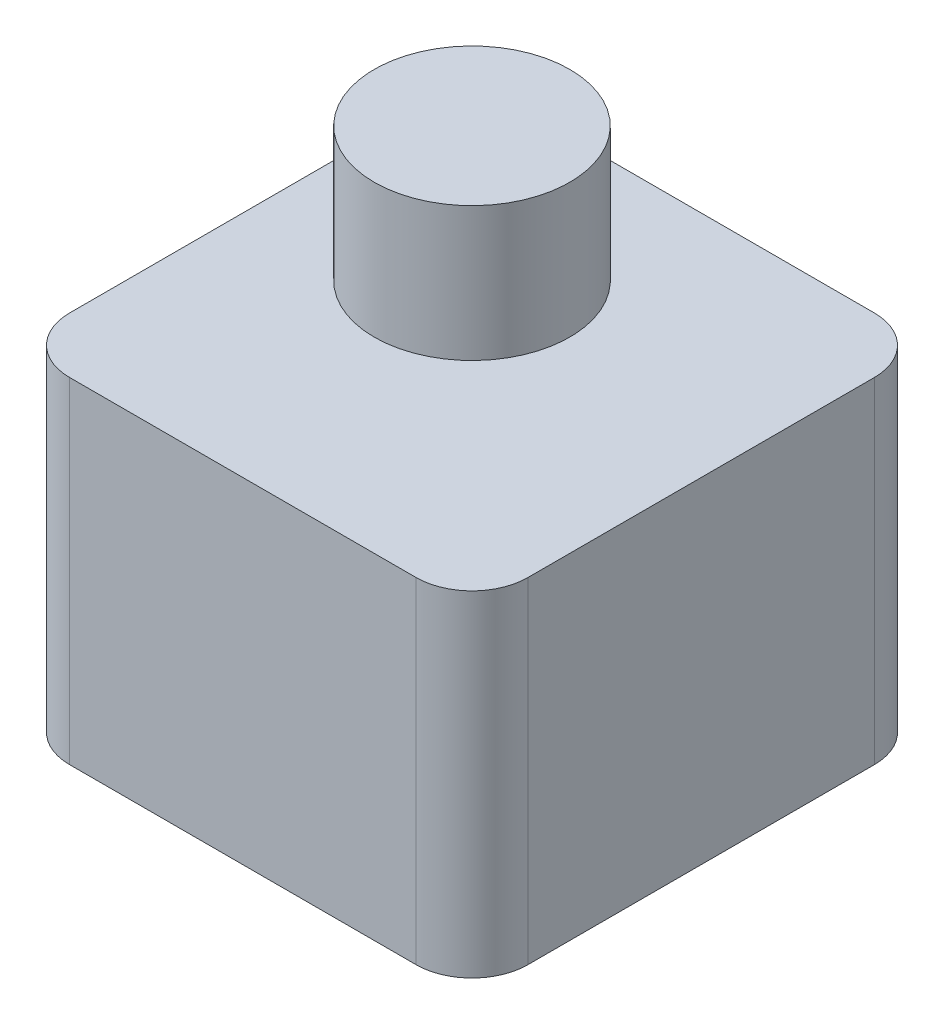
SolidWorks part; units mm, degrees
ref_plane "Alzado" through (0, 0, 0) normal (0, 0, 1) x (1, 0, 0)
ref_plane "Planta" through (0, 0, 0) normal (0, 1, 0) x (1, 0, 0)
ref_plane "Vista lateral" through (0, 0, 0) normal (1, 0, 0) x (0, 0, -1)
sketch "Croquis2" plane through (0, 0, 0) normal (0, 1, 0) x (1, 0, 0)
  line L1 (5, 41) -> (36, 41)
  line L2 (0, 36) -> (0, 5)
  line L3 (5, 0) -> (36, 0)
  line L4 (41, 36) -> (41, 5)
  arc A0 (0, 5) -> (5, 0) centre (5, 5) ccw
  arc A1 (36, 0) -> (41, 5) centre (36, 5) ccw
  arc A2 (36, 41) -> (41, 36) centre (36, 36) cw
  arc A3 (5, 41) -> (0, 36) centre (5, 36) ccw
  dimension "D1" = 5
  dimension "D2" = 41
  dimension "D3" = 41
extrude "Saliente-Extruir2" add sketch "Croquis2" along normal blind 30
sketch "Croquis3" plane through (0, 30, 0) normal (0, 1, 0) x (1, 0, 0)
  circle A3 centre (20.5, 20.5) radius 1.5
extrude "Saliente-Extruir3" add sketch "Croquis3" along normal blind 17 separate body
ref_plane "Plano2" through (0, 35, 0) normal (0, 1, 0) x (1, 0, 0)
sketch "Croquis6" plane through (0, 35, 0) normal (0, 1, 0) x (1, 0, 0)
  circle A0 centre (20.5, 20.5) radius 8.75
extrude "Saliente-Extruir4" add sketch "Croquis6" along normal blind 12
